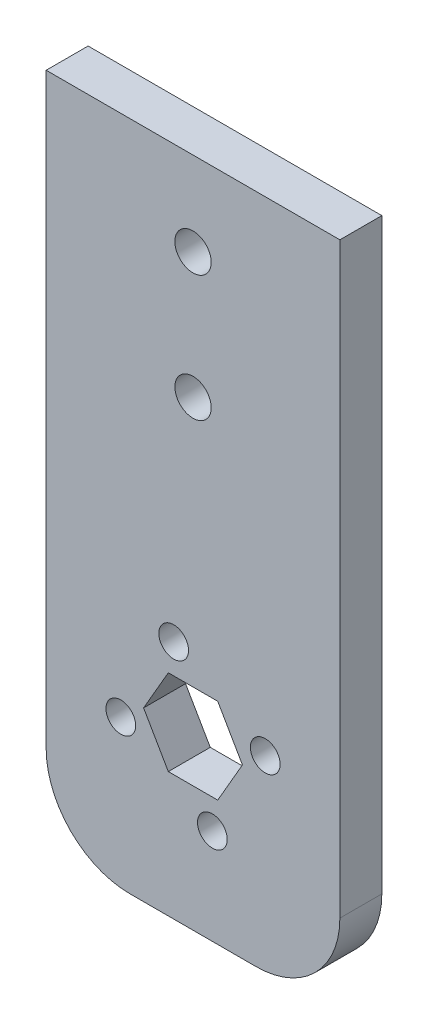
SolidWorks part; units mm, degrees
material "6061 Alloy"
ref_plane "Front Plane" through (0, 0, 0) normal (0, 0, 1) x (1, 0, 0)
ref_plane "Top Plane" through (0, 0, 0) normal (0, 1, 0) x (1, 0, 0)
ref_plane "Right Plane" through (0, 0, 0) normal (1, 0, 0) x (0, 0, -1)
sketch "Sketch1" plane through (0, 0, 0) normal (0, 0, 1) x (1, 0, 0)
  line L1 (0, 0) -> (-44.45, 0)
  line L2 (0, 0) -> (0, 101.6)
  line L3 (0, 101.6) -> (-44.45, 101.6)
  line L4 (-44.45, 0) -> (-44.45, 101.6)
  dimension "D1" = 101.6
  dimension "D2" = 44.45
extrude "Boss-Extrude2" add sketch "Sketch1" along normal blind 6.35
sketch "Sketch3" plane through (0, 0, 0) normal (0, 0, -1) x (-1, 0, 0)
  line L0 (22.225, 101.6) -> (22.225, 0) construction
  line L1 (0, 101.6) -> (44.45, 101.6) construction
  line L2 (44.45, 0) -> (0, 0) construction
  point P3 (22.225, 50.8)
fillet "Fillet1" radius 12.7 2 edges at (-44.45, 0, 3.175) (0, 0, 3.175)
hole_wizard "M5 Clearance Hole1" positions "Sketch11" profile "Sketch12" hole size "M5" standard "ANSI Metric" end condition through all
sketch "Sketch11" plane through (0, 0, 0) normal (0, 0, -1) x (-1, 0, 0)
  line L0 (22.225, 101.6) -> (22.225, 0) construction
  line L1 (0, 101.6) -> (44.45, 101.6) construction
  point P0 (22.225, 88.9)
  point P4 (22.225, 69.85)
  dimension "D1" = 19.05
  dimension "D2" = 12.7
sketch "Sketch12" plane through (-22.225, 88.9, 0) normal (1, 0, 0) x (0, 1, 0)
  line L0 (0, 0) -> (0, 6.35)
  line L1 (0, 6.35) -> (2.75, 6.35)
  line L2 (2.75, 6.35) -> (2.75, 0)
  line L5 (2.75, 0) -> (0, 0)
  line L11 (0, -6.35) -> (0, 107.95) construction
  dimension "Thru Hole Dia." = 5.5
  dimension "Thru Hole Depth" = 6.35
sketch "Sketch14" plane through (0, 0, 6.35) normal (0, 0, 1) x (1, 0, 0)
  line L0 (-22.225, 101.6) -> (-22.225, 0) construction
  line L1 (-14.746, 25.4) -> (-18.4855, 31.877)
  line L2 (-18.4855, 31.877) -> (-25.9645, 31.877)
  line L3 (-25.9645, 31.877) -> (-29.704, 25.4)
  line L4 (-29.704, 25.4) -> (-25.9645, 18.923)
  line L5 (-25.9645, 18.923) -> (-18.4855, 18.923)
  line L6 (-18.4855, 18.923) -> (-14.746, 25.4)
  line L7 (-31.75, 0) -> (-12.7, 0) construction
  circle A0 centre (-22.225, 25.4) radius 6.477 construction
  point P12 (-22.225, 31.877)
  dimension "D1" = 12.954
  dimension "D2" = 25.4
extrude "Cut-Extrude1" cut sketch "Sketch14" against normal through all
sketch "Sketch22" plane through (0, 0, 6.35) normal (0, 0, 1) x (1, 0, 0)
  circle A0 centre (-25.1532, 36.3282) radius 2.05
  circle A1 centre (-11.2968, 28.3282) radius 2.05
  circle A2 centre (-19.2968, 14.4718) radius 2.05
  circle A3 centre (-33.1532, 22.4718) radius 2.05
hole_wizard "M4 Clearance Hole1" positions "Sketch25" profile "Sketch24" hole size "M4" standard "ANSI Metric" end condition through all
sketch "Sketch25" plane through (0, 0, 0) normal (0, 0, -1) x (-1, 0, 0)
  point P0 (11.2968, 28.3282)
  point P3 (25.1532, 36.3282)
  point P6 (33.1532, 22.4718)
  point P9 (19.2968, 14.4718)
sketch "Sketch24" plane through (-11.2968, 28.3282, 0) normal (1, 0, 0) x (0, 1, 0)
  line L0 (0, 0) -> (0, 6.35)
  line L1 (0, 6.35) -> (2.25, 6.35)
  line L2 (2.25, 6.35) -> (2.25, 0)
  line L5 (2.25, 0) -> (0, 0)
  line L11 (0, -6.35) -> (0, 107.95) construction
  dimension "Thru Hole Dia." = 4.5
  dimension "Thru Hole Depth" = 6.35
